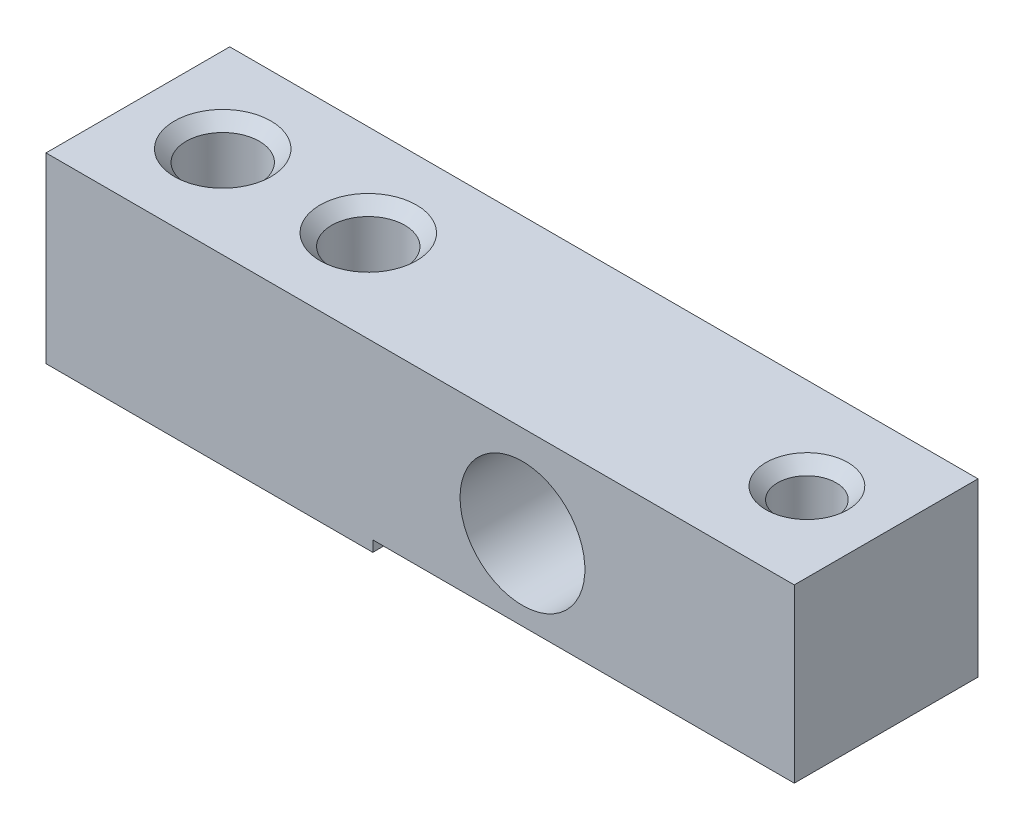
SolidWorks part; units mm, degrees
ref_plane "Front Plane" through (0, 0, 0) normal (0, 0, 1) x (1, 0, 0)
ref_plane "Top Plane" through (0, 0, 0) normal (0, 1, 0) x (1, 0, 0)
ref_plane "Right Plane" through (0, 0, 0) normal (1, 0, 0) x (0, 0, -1)
sketch "Sketch1" plane through (0, 0, 0) normal (1, 0, 0) x (0, 0, -1)
  line L1 (15.9512, -15.8496) -> (-15.9512, -15.8496)
  line L2 (15.9512, -15.8496) -> (15.9512, 15.8496)
  line L3 (15.9512, 15.8496) -> (-15.9512, 15.8496)
  line L4 (-15.9512, -15.8496) -> (-15.9512, 15.8496)
  line L5 (15.9512, -15.8496) -> (-15.9512, 15.8496) construction
  line L6 (15.9512, 15.8496) -> (-15.9512, -15.8496) construction
  point P0 (0, 0)
extrude "Boss-Extrude1" add sketch "Sketch1" along normal blind 129.921
sketch "Sketch2" plane through (0, -15.8496, 0) normal (0, -1, 0) x (1, 0, 0)
  line L0 (129.921, 15.9512) -> (0, 15.9512) construction
  line L1 (129.921, -15.9512) -> (56.7436, -15.9512)
  line L2 (129.921, -15.9512) -> (129.921, 15.9512)
  line L3 (129.921, 15.9512) -> (56.7436, 15.9512)
  line L4 (56.7436, -15.9512) -> (56.7436, 15.9512)
extrude "Cut-Extrude1" cut sketch "Sketch2" against normal blind 1.8796
sketch "Sketch4" plane through (0, 15.8496, 0) normal (0, 1, 0) x (1, 0, 0)
  circle A0 centre (40.005, 0) radius 6.35
  circle A1 centre (14.732, 0) radius 6.35
  circle A3 centre (116.1669, 0) radius 5.08
extrude "Cut-Extrude2" cut sketch "Sketch4" against normal through all
chamfer "Chamfer2" distance 2.032 angle 45 3 edges at (116.1669, 15.8496, 5.08) (14.732, 15.8496, 6.35) (40.005, 15.8496, 6.35)
sketch "Sketch9" plane through (0, 0, -15.9512) normal (0, 0, -1) x (-1, 0, 0)
  circle A0 centre (-82.7278, 0) radius 10.8369
extrude "Cut-Extrude3" cut sketch "Sketch9" against normal through all
